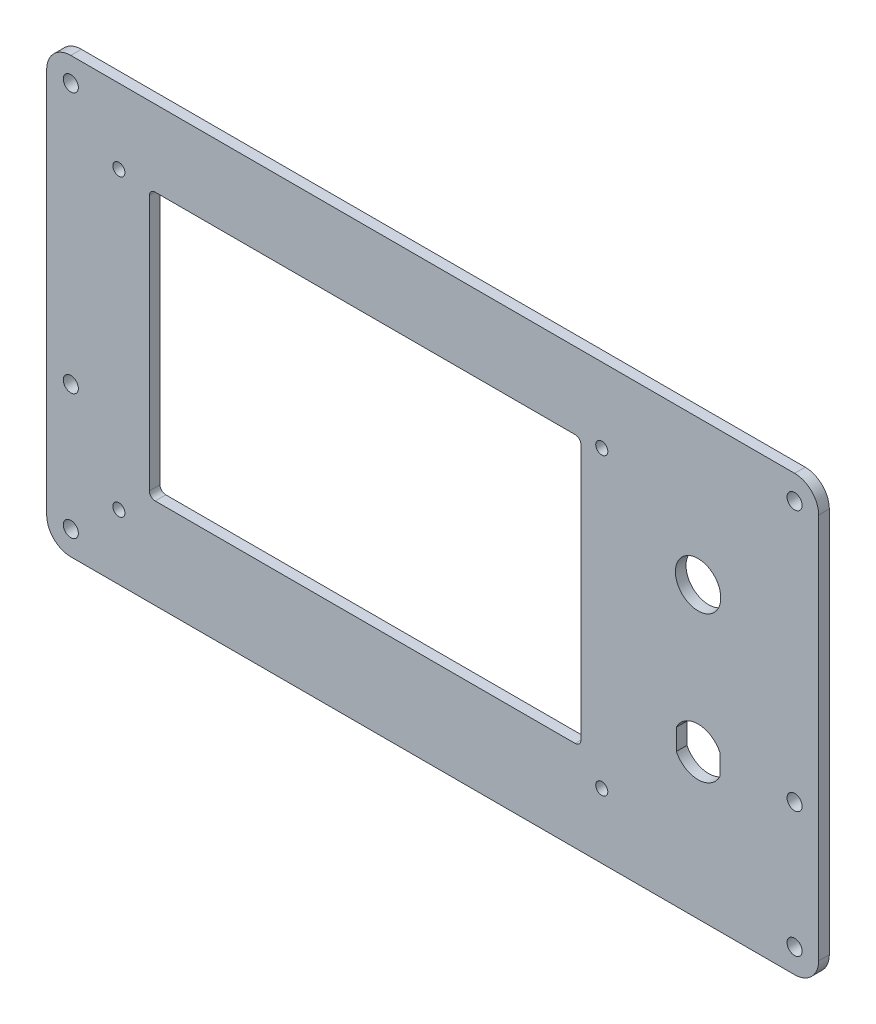
SolidWorks part; units mm, degrees
ref_plane "Front Plane" through (0, 0, 0) normal (0, 0, 1) x (1, 0, 0)
ref_plane "Top Plane" through (0, 0, 0) normal (0, 1, 0) x (1, 0, 0)
ref_plane "Right Plane" through (0, 0, 0) normal (1, 0, 0) x (0, 0, -1)
sketch "Sketch1" plane through (0, 0, 0) normal (0, 0, 1) x (1, 0, 0)
  line L1 (-101.6, -57.15) -> (101.6, -57.15)
  line L2 (-101.6, -57.15) -> (-101.6, 57.15)
  line L3 (-101.6, 57.15) -> (101.6, 57.15)
  line L4 (101.6, -57.15) -> (101.6, 57.15)
  line L5 (-101.6, -57.15) -> (101.6, 57.15) construction
  line L6 (-101.6, 57.15) -> (101.6, -57.15) construction
  point P0 (0, 0)
  dimension "D1" = 203.2
  dimension "D2" = 114.3
extrude "Boss-Extrude1" add sketch "Sketch1" along normal blind 2.794
hole_wizard "1/8 (0.125) Diameter Hole1" positions "Sketch2" profile "Sketch3" hole size "1/8" standard "ANSI Inch" end condition through all
sketch "Sketch2" plane through (0, 0, 2.794) normal (0, 0, 1) x (1, 0, 0)
  line L0 (-19.05, 0) -> (-19.05, 41.7504) construction
  line L4 (-19.05, -1.27) -> (86.3038, -1.27) construction
  line L5 (101.6, 57.15) -> (-101.6, 57.15) construction
  line L7 (-101.6, 57.15) -> (-101.6, -57.15) construction
  point P0 (-82.6, -40.07)
  point P11 (-82.6, 37.53)
  point P13 (44.5, -40.07)
  point P14 (44.5, 37.53)
  dimension "D1" = 127.1
  dimension "D2" = 77.6
  dimension "D3" = 58.42
  dimension "D4" = 82.55
sketch "Sketch3" plane through (-82.6, -40.07, 2.794) normal (1, 0, 0) x (0, -1, 0)
  line L0 (0, 0) -> (0, 2.794)
  line L1 (0, 2.794) -> (1.5875, 2.794)
  line L2 (1.5875, 2.794) -> (1.5875, 0)
  line L5 (1.5875, 0) -> (0, 0)
  line L11 (0, -6.35) -> (0, 107.95) construction
  dimension "Thru Hole Dia." = 3.175
  dimension "Thru Hole Depth" = 2.794
hole_wizard "5/32 (0.15625) Diameter Hole1" positions "Sketch5" profile "Sketch6" hole size "5/32" standard "ANSI Inch" end condition through all
sketch "Sketch5" plane through (0, 0, 2.794) normal (0, 0, 1) x (1, 0, 0)
  line L0 (0, 0) -> (0, 22.4012) construction
  line L1 (0, 0) -> (78.0468, 0) construction
  line L2 (-95.25, -50.8) -> (-95.25, 11.2591) construction
  point P15 (-95.25, 50.8)
  point P19 (95.25, 50.8)
  point P21 (95.25, -50.8)
  point P22 (-95.25, -50.8)
  point P38 (-95.25, -17.78)
  point P42 (95.25, -17.78)
  dimension "D1" = 190.5
  dimension "D2" = 101.6
  dimension "D3" = 33.02
sketch "Sketch6" plane through (95.25, -17.78, 2.794) normal (1, 0, 0) x (0, -1, 0)
  line L0 (0, 0) -> (0, 2.794)
  line L1 (0, 2.794) -> (1.9844, 2.794)
  line L2 (1.9844, 2.794) -> (1.9844, 0)
  line L5 (1.9844, 0) -> (0, 0)
  line L11 (0, -6.35) -> (0, 107.95) construction
  dimension "Thru Hole Dia." = 3.9688
  dimension "Thru Hole Depth" = 2.794
sketch "Sketch4" plane through (0, 0, 2.794) normal (0, 0, 1) x (1, 0, 0)
  line L0 (-101.6, 57.15) -> (-101.6, -57.15) construction
  line L1 (-74.574, -33.304) -> (39.014, -33.304)
  line L2 (-74.574, -33.304) -> (-74.574, 37.084)
  line L3 (-74.574, 37.084) -> (39.014, 37.084)
  line L4 (39.014, -33.304) -> (39.014, 37.084)
  line L5 (-74.574, -33.304) -> (39.014, 37.084) construction
  line L6 (-74.574, 37.084) -> (39.014, -33.304) construction
  line L8 (101.6, 57.15) -> (-101.6, 57.15) construction
  line L9 (101.6, -57.15) -> (101.6, 57.15) construction
  line L10 (-101.6, -57.15) -> (101.6, -57.15) construction
  point P0 (-17.78, 1.89)
  dimension "D1" = 113.588
  dimension "D2" = 70.388
  dimension "D3" = 55.26
  dimension "D4" = 83.82
  dimension "D5" = 27.026
  dimension "D6" = 62.586
  dimension "D7" = 20.066
  dimension "D8" = 23.846
extrude "Cut-Extrude1" cut sketch "Sketch4" against normal through all
fillet "Fillet1" radius 1.524 4 edges at (-74.574, -33.304, 1.397) (39.014, -33.304, 1.397) (39.014, 37.084, 1.397) (-74.574, 37.084, 1.397)
fillet "Fillet2" radius 6.35 4 edges at (-101.6, -57.15, 1.397) (101.6, -57.15, 1.397) (101.6, 57.15, 1.397) (-101.6, 57.15, 1.397)
sketch "Sketch7" plane through (0, 0, 2.794) normal (0, 0, 1) x (1, 0, 0)
  line L0 (69.85, -63.8752) -> (69.85, 92.2072) construction
  line L1 (-95.25, -57.15) -> (95.25, -57.15) construction
  line L2 (101.6, -50.8) -> (101.6, 50.8) construction
  line L3 (64.135, -21.8179) -> (64.135, -16.2821)
  line L4 (75.565, -21.8179) -> (75.565, -16.2821)
  circle A0 centre (69.85, 19.05) radius 5.969
  arc A1 (64.135, -21.8179) -> (75.565, -21.8179) centre (69.85, -19.05) ccw
  arc A2 (75.565, -16.2821) -> (64.135, -16.2821) centre (69.85, -19.05) ccw
  dimension "D1" = 12.7
  dimension "D2" = 11.938
  dimension "D3" = 38.1
  dimension "D4" = 38.1
  dimension "D5" = 31.75
  dimension "D6" = 11.43
extrude "Cut-Extrude2" cut sketch "Sketch7" against normal through all
